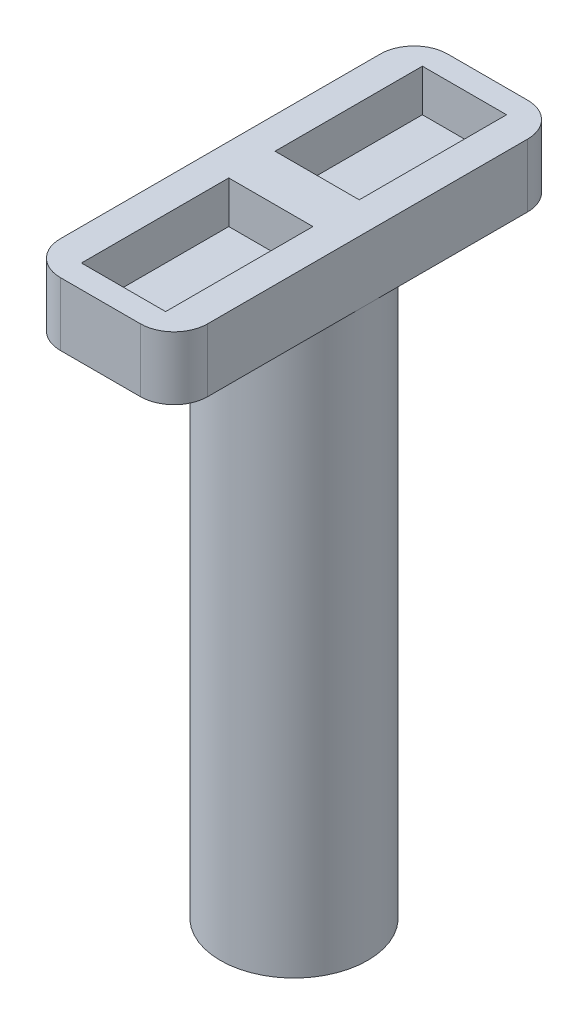
SolidWorks part; units mm, degrees
ref_plane "Front Plane" through (0, 0, 0) normal (0, 0, 1) x (1, 0, 0)
ref_plane "Top Plane" through (0, 0, 0) normal (0, 1, 0) x (1, 0, 0)
ref_plane "Right Plane" through (0, 0, 0) normal (1, 0, 0) x (0, 0, -1)
sketch "Sketch1" plane through (0, 0, 0) normal (0, 1, 0) x (1, 0, 0)
  circle A0 centre (0, 0) radius 17.5
  dimension "D1" = 35
extrude "Boss-Extrude1" add sketch "Sketch1" along normal blind 150
sketch "Sketch2" plane through (0, 0, 0) normal (0, 0, 1) x (1, 0, 0)
  line L0 (-17.5, 150) -> (17.5, 150)
  line L1 (17.5, 150) -> (-17.5, 150) construction
  line L2 (17.5, 150) -> (17.5, 135)
  line L3 (17.5, 0) -> (17.5, 150) construction
  line L4 (17.5, 135) -> (-17.5, 135)
  line L5 (-17.5, 150) -> (-17.5, 0) construction
  line L6 (-17.5, 135) -> (-17.5, 150)
  dimension "D1" = 15
extrude "Boss-Extrude2" add sketch "Sketch2" along normal mid plane 92
sketch "Sketch3" plane through (0, 150, 0) normal (0, 1, 0) x (1, 0, 0)
  line L0 (-17.5, 0) -> (17.5, 0) construction
  line L1 (17.5, -46) -> (17.5, 46) construction
  line L3 (-10, 40.5) -> (10, 40.5)
  line L4 (-10, 40.5) -> (-10, 5.5)
  line L5 (-10, 5.5) -> (10, 5.5)
  line L6 (10, 40.5) -> (10, 5.5)
  line L7 (0, 46) -> (0, 0) construction
  line L8 (17.5, 46) -> (-17.5, 46) construction
  line L9 (10, -40.5) -> (10, -5.5)
  line L10 (-10, -5.5) -> (10, -5.5)
  line L11 (-10, -40.5) -> (-10, -5.5)
  line L12 (-10, -40.5) -> (10, -40.5)
  dimension "D1" = 20
  dimension "D2" = 35
  dimension "D3" = 10
  dimension "D4" = 5.5
extrude "Cut-Extrude1" cut sketch "Sketch3" against normal blind 10
fillet "Fillet1" radius 8 4 edges at (-17.5, 142.5, -46) (17.5, 142.5, -46) (17.5, 142.5, 46) (-17.5, 142.5, 46)
